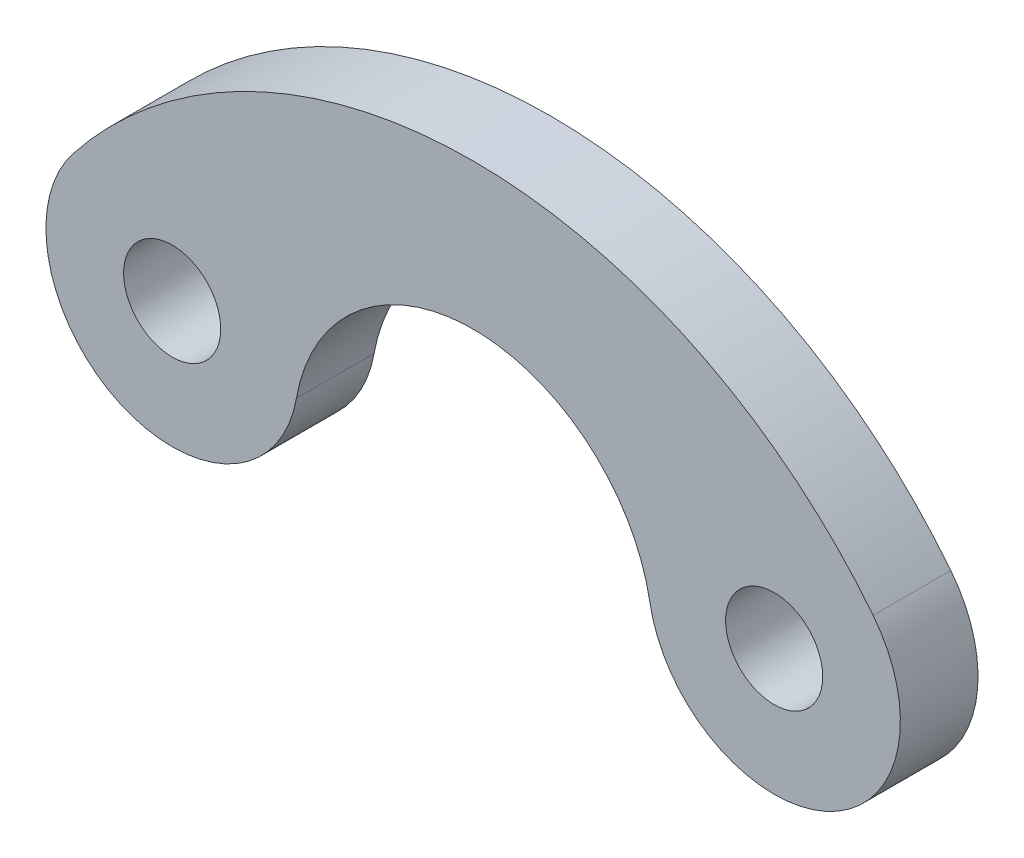
SolidWorks part; units mm, degrees
ref_plane "Front Plane" through (0, 0, 0) normal (0, 0, 1) x (1, 0, 0)
ref_plane "Top Plane" through (0, 0, 0) normal (0, 1, 0) x (1, 0, 0)
ref_plane "Right Plane" through (0, 0, 0) normal (1, 0, 0) x (0, 0, -1)
sketch "Sketch1" plane through (0, 0, 0) normal (0, 0, 1) x (1, 0, 0)
  line L0 (-15.748, 0) -> (0, 0) construction
  circle A0 centre (0, 0) radius 1.27
  circle A1 centre (-15.748, 0) radius 1.27
  arc A2 (-18.3373, 2.0491) -> (-12.4964, -0.5749) centre (-15.748, 0) ccw
  arc A3 (-3.2516, -0.5749) -> (2.5893, 2.0491) centre (0, 0) ccw
  arc A4 (-12.4964, -0.5749) -> (-3.2516, -0.5749) centre (-7.874, -1.3921) cw
  arc A5 (-18.3373, 2.0491) -> (2.5893, 2.0491) centre (-7.874, -6.2315) cw
  circle A6 centre (-7.874, 0) radius 3.302 construction
  point P15 (-7.874, 3.302)
  point P16 (-7.874, 3.302)
  point P17 (-7.874, 7.112)
  dimension "D1" = 2.54
  dimension "D3" = 6.604
  dimension "D4" = 6.604
  dimension "D2" = 15.748
  dimension "D5" = 3.81
extrude "Boss-Extrude1" add sketch "Sketch1" along normal blind 2.032
